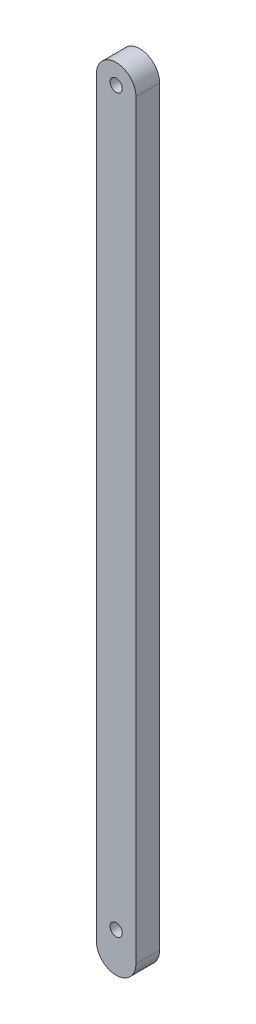
SolidWorks part; units mm, degrees
ref_plane "Front Plane" through (0, 0, 0) normal (0, 0, 1) x (1, 0, 0)
ref_plane "Top Plane" through (0, 0, 0) normal (0, 1, 0) x (1, 0, 0)
ref_plane "Right Plane" through (0, 0, 0) normal (1, 0, 0) x (0, 0, -1)
sketch "Esquisse3" plane through (0, 0, 0) normal (0, 0, 1) x (1, 0, 0)
  line L2 (-7, -132) -> (-7, 58)
  line L4 (3, -132) -> (3, 58)
  arc A0 (3, 58) -> (-7, 58) centre (-2, 58) ccw
  arc A1 (-7, -132) -> (3, -132) centre (-2, -132) ccw
  point P0 (0, 0)
  point P1 (-2, 63)
  point P2 (-2, -137)
  dimension "D3" = 10
  dimension "D4" = 10
  dimension "D1" = 200
  dimension "D2" = 10
extrude "Boss.-Extru.1" add sketch "Esquisse3" along normal blind 6
sketch "Esquisse4" plane through (0, 0, 0) normal (0, 0, -1) x (-1, 0, 0)
  line L1 (2, 63) -> (2, 50063) construction
  circle A3 centre (2, -127) radius 1.55
  arc A4 (-3, -132) -> (7, -132) centre (2, -132) ccw construction
  circle A5 centre (2, 58) radius 1.55
  arc A6 (7, 58) -> (-3, 58) centre (2, 58) ccw construction
  point P5 (2, -137)
  point P7 (2, 63)
  dimension "D1" = 3.1
  dimension "D2" = 10
  dimension "D3" = 5
extrude "Enlèv. mat.-Extru.3" cut sketch "Esquisse4" against normal up to surface (6 mm away) up to face at (-2, -37, 6)
equation "\"ScrewSize\"= 3.1mm"
